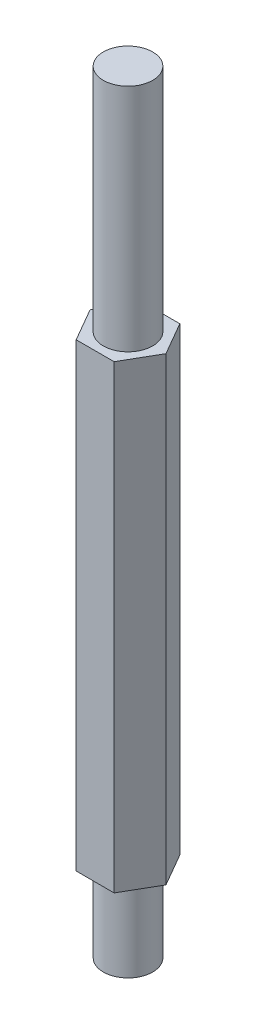
SolidWorks part; units mm, degrees
ref_plane "Front Plane" through (0, 0, 0) normal (0, 0, 1) x (1, 0, 0)
ref_plane "Top Plane" through (0, 0, 0) normal (0, 1, 0) x (1, 0, 0)
ref_plane "Right Plane" through (0, 0, 0) normal (1, 0, 0) x (0, 0, -1)
sketch "Sketch2" plane through (0, 0, 0) normal (0, 1, 0) x (1, 0, 0)
  line L1 (-12.7747, 6.4658) -> (-13.9294, 8.4658)
  line L2 (-13.9294, 8.4658) -> (-16.2388, 8.4658)
  line L3 (-16.2388, 8.4658) -> (-17.3935, 6.4658)
  line L4 (-17.3935, 6.4658) -> (-16.2388, 4.4658)
  line L5 (-16.2388, 4.4658) -> (-13.9294, 4.4658)
  line L6 (-13.9294, 4.4658) -> (-12.7747, 6.4658)
  circle A0 centre (-15.0841, 6.4658) radius 2 construction
  point P1 (0, 0)
  dimension "D1" = 4
extrude "Boss-Extrude1" add sketch "Sketch2" along normal blind 28
ref_plane "Plane1" through (0, 28, 0) normal (0, 1, 0) x (1, 0, 0)
sketch "Sketch3" plane through (0, 28, 0) normal (0, 1, 0) x (1, 0, 0)
  line L1 (-13.9294, 8.4658) -> (-16.2388, 8.4658) construction
  line L2 (-16.2388, 4.4658) -> (-13.9294, 4.4658) construction
  circle A0 centre (-15.0835, 6.4658) radius 1.5
  point P2 (0, 0)
  point P4 (-14.9992, 6.3774)
  dimension "D1" = 2.31
  dimension "D2" = 2.3088
  dimension "D3" = 2
  dimension "D4" = 2
extrude "Boss-Extrude2" add sketch "Sketch3" along normal blind 14
ref_plane "Plane2" through (0, 0, 0) normal (0, -1, 0) x (-1, 0, 0)
sketch "Sketch4" plane through (0, 0, 0) normal (0, -1, 0) x (-1, 0, 0)
  line L0 (13.9294, 8.4658) -> (16.2388, 8.4658) construction
  circle A0 centre (15.0835, 6.4658) radius 1.5
  point P2 (0, 0)
  dimension "D1" = 2.31
  dimension "D2" = 2
extrude "Boss-Extrude3" add sketch "Sketch4" along normal blind 5
